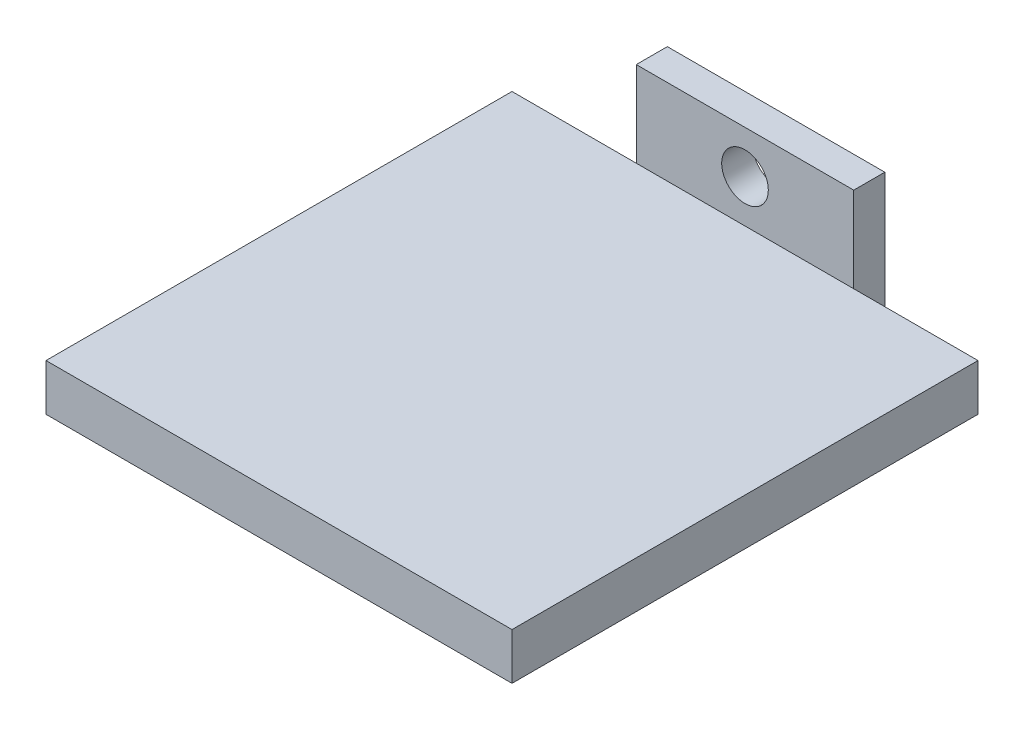
SolidWorks part; units mm, degrees
ref_plane "Front Plane" through (0, 0, 0) normal (0, 0, 1) x (1, 0, 0)
ref_plane "Top Plane" through (0, 0, 0) normal (0, 1, 0) x (1, 0, 0)
ref_plane "Right Plane" through (0, 0, 0) normal (1, 0, 0) x (0, 0, -1)
sketch "Sketch1" plane through (0, 0, 0) normal (0, 0, 1) x (1, 0, 0)
  line L1 (-7, -7) -> (7, -7)
  line L2 (-7, -7) -> (-7, 7)
  line L3 (-7, 7) -> (7, 7)
  line L4 (7, -7) -> (7, 7)
  line L5 (-7, -7) -> (7, 7) construction
  line L6 (-7, 7) -> (7, -7) construction
  point P0 (0, 0)
  dimension "D1" = 14
  dimension "D2" = 14
extrude "Boss-Extrude1" add sketch "Sketch1" along normal blind 2
sketch "Sketch2" plane through (0, 0, 2) normal (0, 0, 1) x (1, 0, 0)
  line L1 (-15, -1.5) -> (15, -1.5)
  line L2 (-15, -1.5) -> (-15, 1.5)
  line L3 (-15, 1.5) -> (15, 1.5)
  line L4 (15, -1.5) -> (15, 1.5)
  line L5 (-15, -1.5) -> (15, 1.5) construction
  line L6 (-15, 1.5) -> (15, -1.5) construction
  point P0 (0, 0)
  dimension "D1" = 30
  dimension "D2" = 3
extrude "Boss-Extrude2" add sketch "Sketch2" along normal blind 30
ref_point "Point1"
ref_point "Point2"
hole_wizard "Ø3.0mm Dowel Hole1" positions "Sketch3" profile "Sketch4" hole size "Ø3.0" standard "ISO" end condition through all
sketch "Sketch3" plane through (0, 0, 2) normal (0, 0, 1) x (1, 0, 0)
  point P0 (0, -4.25)
  point P3 (0, 4.25)
sketch "Sketch4" plane through (0, -4.25, 2) normal (1, 0, 0) x (0, -1, 0)
  line L0 (0, 0) -> (0, 2)
  line L1 (0, 2) -> (1.5, 2)
  line L2 (1.5, 2) -> (1.5, 0)
  line L5 (1.5, 0) -> (0, 0)
  line L11 (0, -6.35) -> (0, 107.95) construction
  dimension "Thru Hole Dia." = 3
  dimension "Thru Hole Depth" = 2
